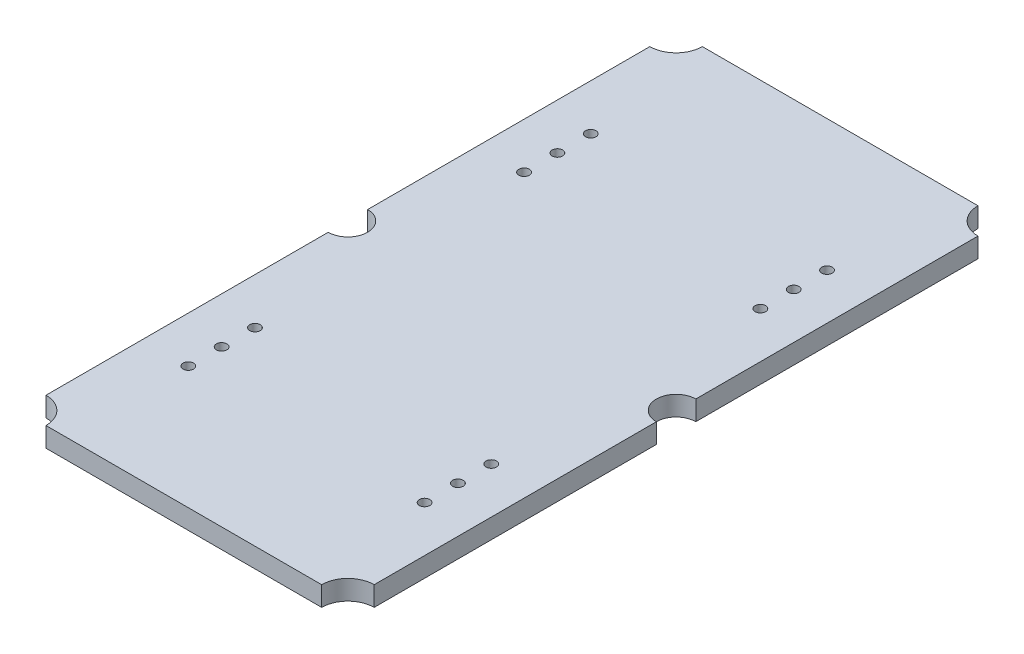
SolidWorks part; units mm, degrees
ref_plane "Спереди" through (0, 0, 0) normal (0, 0, 1) x (1, 0, 0)
ref_plane "Сверху" through (0, 0, 0) normal (0, 1, 0) x (1, 0, 0)
ref_plane "Справа" through (0, 0, 0) normal (1, 0, 0) x (0, 0, -1)
sketch "Эскиз1" plane through (0, 0, 0) normal (0, 1, 0) x (1, 0, 0)
  line L1 (0, 0) -> (25, 0)
  line L2 (0, 0) -> (0, 50)
  line L3 (0, 50) -> (25, 50)
  line L4 (25, 0) -> (25, 50)
  dimension "D1" = 25
  dimension "D2" = 50
extrude "Бобышка-Вытянуть1" add sketch "Эскиз1" along normal blind 1.5
sketch "Эскиз2" plane through (0, 1.5, 0) normal (0, 1, 0) x (1, 0, 0)
  line L0 (0, 0) -> (25, 0) construction
  line L1 (25, 0) -> (25, 50) construction
  line L2 (0, 50) -> (0, 0) construction
  line L3 (25, 50) -> (0, 50) construction
  circle A0 centre (25, 25) radius 1.5
  circle A1 centre (0, 25) radius 1.5
  circle A2 centre (25, 0) radius 2
  circle A3 centre (0, 0) radius 2
  circle A4 centre (0, 50) radius 2
  circle A5 centre (25, 50) radius 2
  circle A6 centre (3.5, 40) radius 0.4
  circle A7 centre (3.5, 37.46) radius 0.4
  circle A8 centre (3.5, 34.92) radius 0.4
  circle A9 centre (3.5, 14.42) radius 0.4
  circle A10 centre (3.5, 11.88) radius 0.4
  circle A11 centre (3.5, 9.34) radius 0.4
  circle A12 centre (21.5, 40) radius 0.4
  circle A13 centre (21.5, 37.46) radius 0.4
  circle A14 centre (21.5, 34.92) radius 0.4
  circle A15 centre (21.5, 14.42) radius 0.4
  circle A16 centre (21.5, 11.88) radius 0.4
  circle A17 centre (21.5, 9.34) radius 0.4
  dimension "D1" = 3
  dimension "D2" = 3
  dimension "D4" = 4
  dimension "D5" = 4
  dimension "D6" = 0.8
  dimension "D3" = 25
  dimension "D7" = 10
  dimension "D8" = 3.5
  dimension "D14" = 20.5
  dimension "D18" = 18
  dimension "D9" = 3
  dimension "D10" = 2
  dimension "D11" = 3
  dimension "D12" = 2
  dimension "D13" = 3
  dimension "D15" = 2
  dimension "D16" = 3
extrude "Вырез-Вытянуть1" cut sketch "Эскиз2" against normal through all
